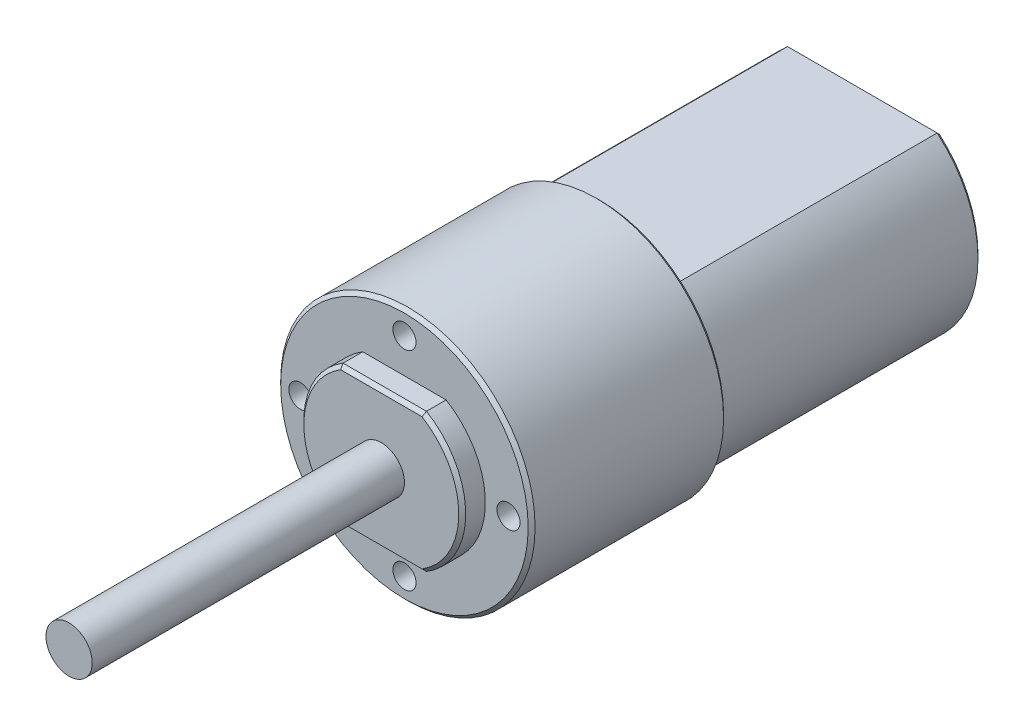
SolidWorks part; units mm, degrees
ref_plane "Front Plane" through (0, 0, 0) normal (0, 0, 1) x (1, 0, 0)
ref_plane "Top Plane" through (0, 0, 0) normal (0, 1, 0) x (1, 0, 0)
ref_plane "Right Plane" through (0, 0, 0) normal (1, 0, 0) x (0, 0, -1)
sketch "Sketch1" plane through (0, 0, 0) normal (0, 1, 0) x (1, 0, 0)
  line L0 (0, 0.2875) -> (0, 37.1846) construction
  line L1 (-2, -29) -> (-2, -2)
  line L2 (-2, -29) -> (0, -29)
  line L3 (-2, -2) -> (-7, -2)
  line L4 (-7, -2) -> (-7, 0)
  line L5 (-7, 0) -> (-11, 0)
  line L6 (-11, 0) -> (-11, 16.9)
  line L7 (-11, 16.9) -> (-10, 16.9)
  line L8 (-10, 16.9) -> (-10, 39.9)
  line L9 (-10, 39.9) -> (0, 39.9)
  line L10 (0, 39.9) -> (0, -29)
  dimension "D1" = 4
  dimension "D2" = 27
  dimension "D3" = 2
  dimension "D4" = 22
  dimension "D5" = 14
  dimension "D6" = 16.9
  dimension "D7" = 41.9
  dimension "D8" = 20
revolve "Revolve1" add sketch "Sketch1" angle 360 about L0
sketch "Sketch2" plane through (0, 0, -39.9) normal (0, 0, -1) x (-1, 0, 0)
  line L0 (-6.4699, 7.625) -> (6.4699, 7.625)
  line L1 (-6.4699, -7.625) -> (6.4699, -7.625)
  line L2 (0, 0) -> (16.0467, 0) construction
  circle A0 centre (0, 0) radius 10 construction
  circle A2 centre (0, 0) radius 10
  circle A3 centre (0, 0) radius 10
  circle M5 centre (0, 0) radius 10
  dimension "D1" = 15.25
  dimension "D2" = 0
extrude "Cut-Extrude1" cut sketch "Sketch2" against normal up to surface (23 mm away) contours L0 M5 | L1 M5 up to face at (11, 0, -16.9)
sketch "Sketch3" plane through (0, 0, 0) normal (0, 0, 1) x (1, 0, 0)
  circle A0 centre (0, 9) radius 1
  circle A1 centre (0, 0) radius 9 construction
  circle A2 centre (9, 0) radius 1
  circle A3 centre (0, -9) radius 1
  circle A4 centre (-9, 0) radius 1
  point P6 (-10.6029, 0.5337)
  point P7 (0, 0)
  point P15 (0, 0)
  dimension "D1" = 18
  dimension "D2" = 2
  dimension "D3" = 4
extrude "Cut-Extrude2" cut sketch "Sketch3" against normal blind 10
sketch "Sketch4" plane through (0, 0, 2) normal (0, 0, 1) x (1, 0, 0)
  line L0 (-3.6056, 6) -> (3.6056, 6)
  line L1 (-3.6056, -6) -> (3.6056, -6)
  line L2 (0, 0) -> (4.6997, 0) construction
  circle A0 centre (0, 0) radius 7 construction
  circle A1 centre (0, 0) radius 7 construction
  circle A3 centre (0, 0) radius 7
  circle A4 centre (0, 0) radius 7
  point P11 (-3.6056, -6)
  circle M6 centre (0, 0) radius 7
  dimension "D1" = 12
  dimension "D2" = 0
extrude "Cut-Extrude3" cut sketch "Sketch4" against normal up to surface (2 mm away) contours L0 M6 | L1 M6 up to face at (1, 9, 0)
chamfer "Chamfer1" distance 0.3 angle 45 10 edges at (11, 0, 0) (-10, 0, -39.9) (10, 0, -39.9) (0, 7.625, -39.9) (0, -7.625, -39.9) (-7, 0, 2) (7, 0, 2) (0, 6, 2) (0, -6, 2) (11, 0, -16.9)
